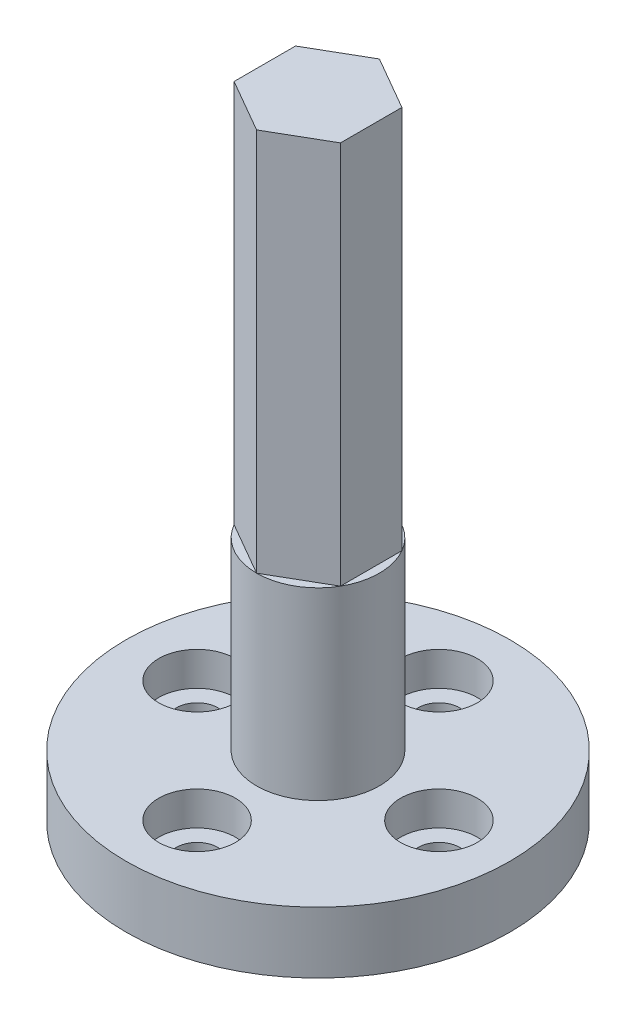
SolidWorks part; units mm, degrees
ref_plane "Alzado" through (0, 0, 0) normal (0, 0, 1) x (1, 0, 0)
ref_plane "Planta" through (0, 0, 0) normal (0, 1, 0) x (1, 0, 0)
ref_plane "Vista lateral" through (0, 0, 0) normal (1, 0, 0) x (0, 0, -1)
sketch "Croquis3" plane through (0, 0, 0) normal (0, 1, 0) x (1, 0, 0)
  circle A0 centre (0, 0) radius 12.5
  dimension "D1" = 25
extrude "Saliente-Extruir1" add sketch "Croquis3" along normal blind 4
sketch "Croquis4" plane through (0, 4, 0) normal (0, 1, 0) x (1, 0, 0)
  circle A0 centre (0, 0) radius 4
  dimension "D1" = 8
extrude "Saliente-Extruir2" add sketch "Croquis4" along normal blind 37
sketch "Croquis7" plane through (0, 0, 0) normal (0, -1, 0) x (1, 0, 0)
  circle A0 centre (0, 0) radius 12
  dimension "D1" = 24
sketch "Croquis12" plane through (0, 41, 0) normal (0, 1, 0) x (1, 0, 0)
  line L1 (0, 4) -> (-3.4641, 2)
  line L2 (-3.4641, 2) -> (-3.4641, -2)
  line L3 (-3.4641, -2) -> (0, -4)
  line L4 (0, -4) -> (3.4641, -2)
  line L5 (3.4641, -2) -> (3.4641, 2)
  line L6 (3.4641, 2) -> (0, 4)
  circle A0 centre (0, 0) radius 4 construction
  circle A1 centre (0, 0) radius 4 construction
  circle A2 centre (0, 0) radius 4 construction
extrude "Cortar-Extruir7" cut sketch "Croquis12" against normal blind 25 flip side to cut
sketch "Croquis13" plane through (0, 0, 0) normal (0, -1, 0) x (1, 0, 0)
  circle A0 centre (0, 7.875) radius 1.35
  circle A1 centre (7.875, 0) radius 1.35
  circle A2 centre (0, -7.875) radius 1.35
  circle A3 centre (-7.875, 0) radius 1.35
  point P12 (0, 0)
  dimension "D1" = 7.875
  dimension "D3" = 2.7
  dimension "D2" = 4
extrude "Cortar-Extruir8" cut sketch "Croquis13" against normal blind 10
sketch "Croquis14" plane through (0, 4, 0) normal (0, 1, 0) x (1, 0, 0)
  circle A0 centre (0, 7.875) radius 1.35 construction
  circle A1 centre (0, 7.875) radius 1.35 construction
  circle A2 centre (0, 7.875) radius 2.5
  circle A3 centre (7.875, 0) radius 2.5
  circle A4 centre (0, -7.875) radius 2.5
  circle A5 centre (-7.875, 0) radius 2.5
  point P13 (0, 0)
  dimension "D1" = 5
  dimension "D2" = 4
extrude "Cortar-Extruir9" cut sketch "Croquis14" against normal blind 2.2
